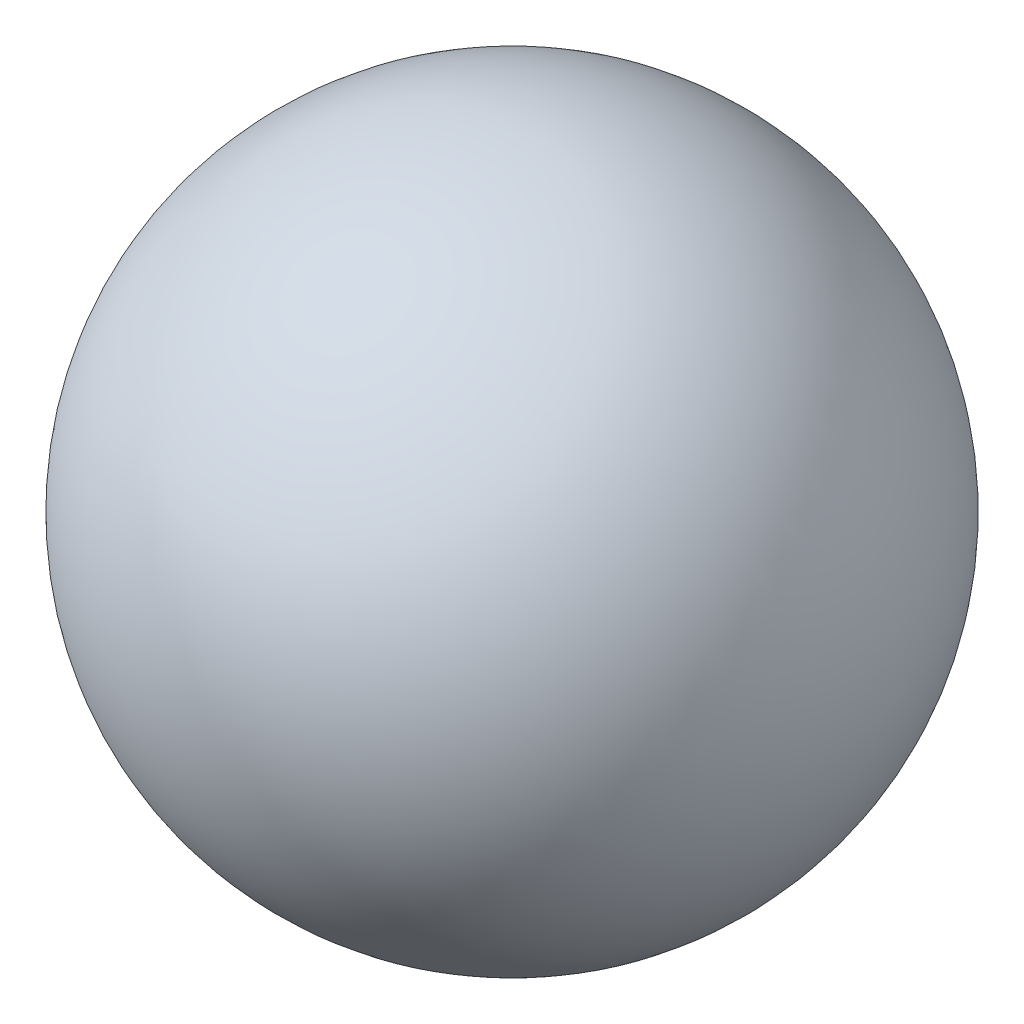
SolidWorks part; units mm, degrees
ref_plane "Front Plane" through (0, 0, 0) normal (0, 0, 1) x (1, 0, 0)
ref_plane "Top Plane" through (0, 0, 0) normal (0, 1, 0) x (1, 0, 0)
ref_plane "Right Plane" through (0, 0, 0) normal (1, 0, 0) x (0, 0, -1)
other "Graphic1"
other "Graphic (Closed) -1"
other "Graphic (Closed) -2"
other "Graphic (Closed) -3"
sketch "Sketch1" plane through (0, 0, 0) normal (0, 0, 1) x (1, 0, 0)
  line L0 (121.2536, 134.7187) -> (121.2536, 94.4725)
  arc A0 (121.2536, 94.4725) -> (121.2536, 134.7187) centre (121.2536, 114.5956) ccw
revolve "Revolve1" add sketch "Sketch1" angle 360 about L0
move or copy body "Body-Move/Copy1" bodies to move or copy 101 copy no translate (0, 0, 22.5449) parameters "D1"=0, "D2"=0, "D3"=22.5449
